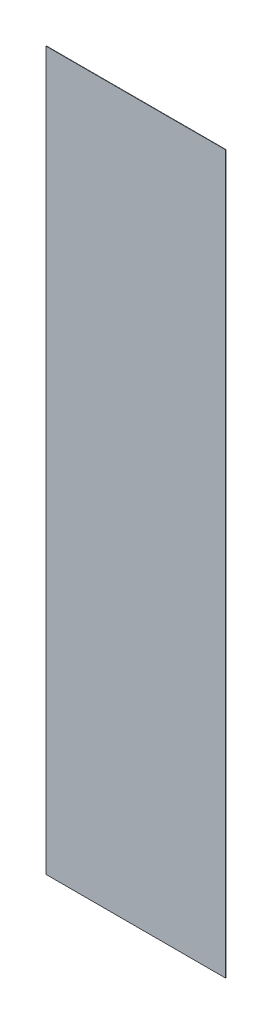
SolidWorks part; units mm, degrees
material "AISI 304"
ref_plane "Front Plane" through (0, 0, 0) normal (0, 0, 1) x (1, 0, 0)
ref_plane "Top Plane" through (0, 0, 0) normal (0, 1, 0) x (1, 0, 0)
ref_plane "Right Plane" through (0, 0, 0) normal (1, 0, 0) x (0, 0, -1)
sketch "Sketch1" plane through (0, 0, 0) normal (0, 0, 1) x (1, 0, 0)
  line L1 (-3.175, -12.7127) -> (3.175, -12.7127)
  line L2 (-3.175, -12.7127) -> (-3.175, 12.7127)
  line L3 (-3.175, 12.7127) -> (3.175, 12.7127)
  line L4 (3.175, -12.7127) -> (3.175, 12.7127)
  line L5 (-3.175, -12.7127) -> (3.175, 12.7127) construction
  line L6 (-3.175, 12.7127) -> (3.175, -12.7127) construction
  point P0 (0, 0)
  dimension "D1" = 6.35
  dimension "D2" = 25.4254
extrude "Boss-Extrude1" add sketch "Sketch1" along normal blind 0.0127
